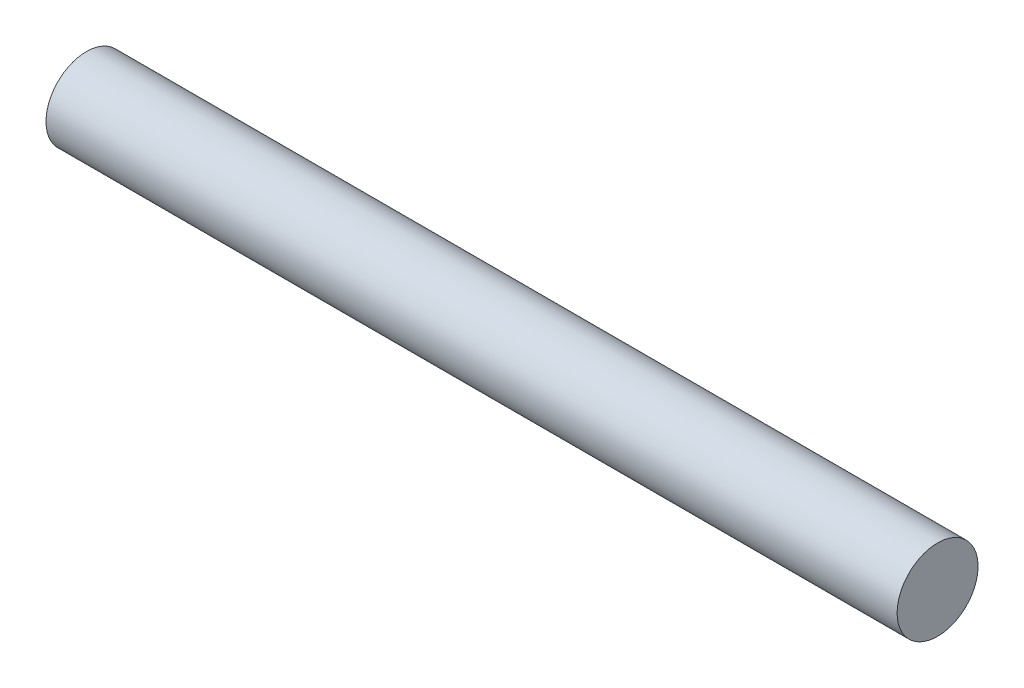
SolidWorks part; units mm, degrees
ref_plane "Ebene vorne" through (0, 0, 0) normal (0, 0, 1) x (1, 0, 0)
ref_plane "Ebene oben" through (0, 0, 0) normal (0, 1, 0) x (1, 0, 0)
ref_plane "Ebene rechts" through (0, 0, 0) normal (1, 0, 0) x (0, 0, -1)
sketch "Sketch1" plane through (0, 0, 0) normal (0, 0, 1) x (1, 0, 0)
  line L0 (-28.2087, 0) -> (208.9853, 0) construction
  line L1 (0, 0) -> (534, 0)
  line L2 (0, 0) -> (0, 25.4)
  line L3 (0, 25.4) -> (534, 25.4)
  line L4 (534, 0) -> (534, 25.4)
  dimension "D1" = 50.8
  dimension "D2" = 534
revolve "Revolve1" add sketch "Sketch1" angle 360 about L0
